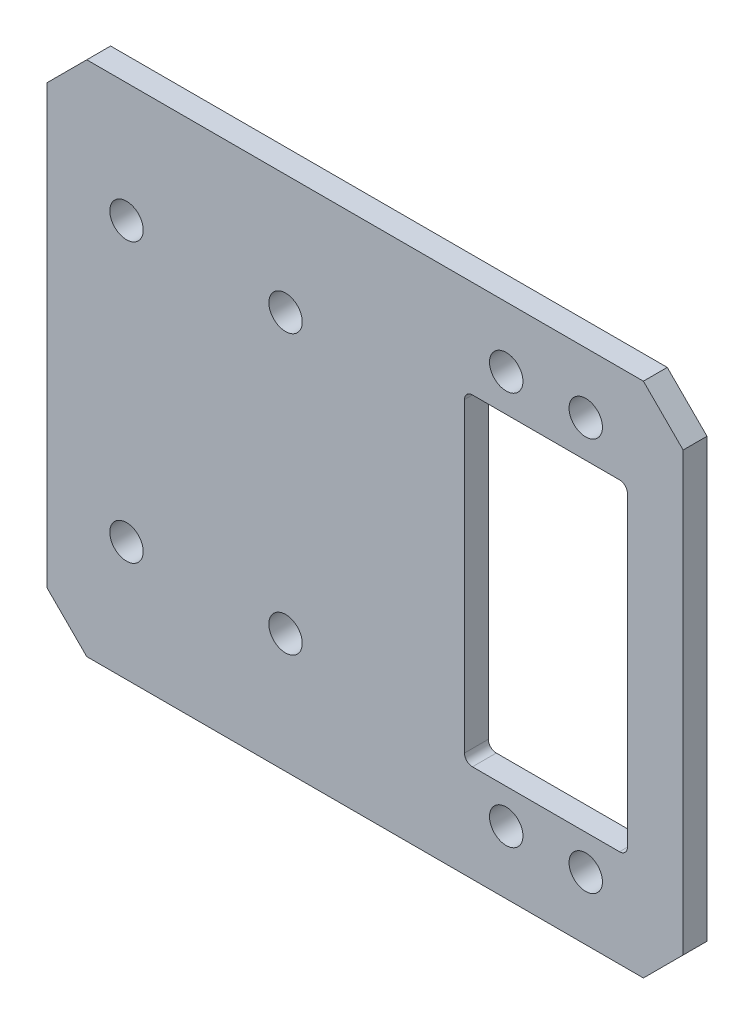
SolidWorks part; units mm, degrees
material "5052-O"
ref_plane "前基準面" through (0, 0, 0) normal (0, 0, 1) x (1, 0, 0)
ref_plane "上基準面" through (0, 0, 0) normal (0, 1, 0) x (1, 0, 0)
ref_plane "右基準面" through (0, 0, 0) normal (1, 0, 0) x (0, 0, -1)
sketch "草圖1" plane through (0, 0, 0) normal (0, 0, 1) x (1, 0, 0)
  line L21 (40, -32.5) -> (-40, -32.5)
  line L22 (40, -32.5) -> (40, 32.5)
  line L23 (40, 32.5) -> (-40, 32.5)
  line L24 (-40, -32.5) -> (-40, 32.5)
  line L25 (40, -32.5) -> (-40, 32.5) construction
  line L26 (40, 32.5) -> (-40, -32.5) construction
  point P0 (0, 0)
  dimension "D1" = 80
  dimension "D2" = 65
extrude "填料-伸長1" add sketch "草圖1" along normal blind 3
sketch "草圖2" plane through (0, 0, 3) normal (0, 0, 1) x (1, 0, 0)
  line L0 (-40, 32.5) -> (-40, -32.5) construction
  line L1 (-30, 17.5) -> (-10, 17.5) construction
  line L2 (-30, 17.5) -> (-30, -17.5) construction
  line L3 (-30, -17.5) -> (-10, -17.5) construction
  line L4 (-10, 17.5) -> (-10, -17.5) construction
  line L5 (-30, 17.5) -> (-10, -17.5) construction
  line L6 (-30, -17.5) -> (-10, 17.5) construction
  circle A0 centre (-30, 17.5) radius 2.1
  point P2 (-20, 0)
  dimension "D4" = 4.2
  dimension "D1" = 20
  dimension "D2" = 20
  dimension "D3" = 35
extrude "除料-伸長1" cut sketch "草圖2" against normal through all
pattern_linear "直線複製排列1" count 2 spacing 20 along (1, 0, 0) count 2 spacing 35 along (0, -1, 0) of "除料-伸長1"
sketch "草圖4" plane through (0, 0, 3) normal (0, 0, 1) x (1, 0, 0)
  line L1 (12.5, -20.25) -> (33, -20.25)
  line L2 (12.5, -20.25) -> (12.5, 20.25)
  line L3 (12.5, 20.25) -> (33, 20.25)
  line L4 (33, -20.25) -> (33, 20.25)
  line L5 (12.5, -20.25) -> (33, 20.25) construction
  line L6 (12.5, 20.25) -> (33, -20.25) construction
  line L7 (40, -32.5) -> (40, 32.5) construction
  point P0 (22.75, 0)
  dimension "D1" = 20.5
  dimension "D2" = 40.5
  dimension "D3" = 7
extrude "除料-伸長2" cut sketch "草圖4" along direction (0, 0, 1) on the side against the normal up to next (3 mm away)
fillet "圓角1" radius 1 4 edges at (33, -20.25, 1.5) (12.5, -20.25, 1.5) (12.5, 20.25, 1.5) (33, 20.25, 1.5)
sketch "草圖5" plane through (0, 0, 3) normal (0, 0, 1) x (1, 0, 0)
  line L0 (32, 20.25) -> (13.5, 20.25) construction
  line L1 (13.5, -20.25) -> (32, -20.25) construction
  line L2 (17.75, 24.9) -> (27.75, 24.9) construction
  line L3 (17.75, 24.9) -> (17.75, -24.6) construction
  line L4 (17.75, -24.6) -> (27.75, -24.6) construction
  line L5 (27.75, 24.9) -> (27.75, -24.6) construction
  circle A0 centre (17.75, 24.9) radius 2.1
  circle A1 centre (27.75, 24.9) radius 2.1
  circle A2 centre (27.75, -24.6) radius 2.1
  circle A3 centre (17.75, -24.6) radius 2.1
  point P7 (22.75, -24.6)
  point P10 (22.75, -20.25)
  dimension "D4" = 4.2
  dimension "D5" = 4.2
  dimension "D6" = 4.2
  dimension "D7" = 4.2
  dimension "D1" = 4.65
  dimension "D2" = 10
  dimension "D3" = 49.5
extrude "除料-伸長3" cut sketch "草圖5" against normal up to next
chamfer "導角3" distance 5 angle 45 4 edges at (40, 32.5, 1.5) (40, -32.5, 1.5) (-40, -32.5, 1.5) (-40, 32.5, 1.5)
